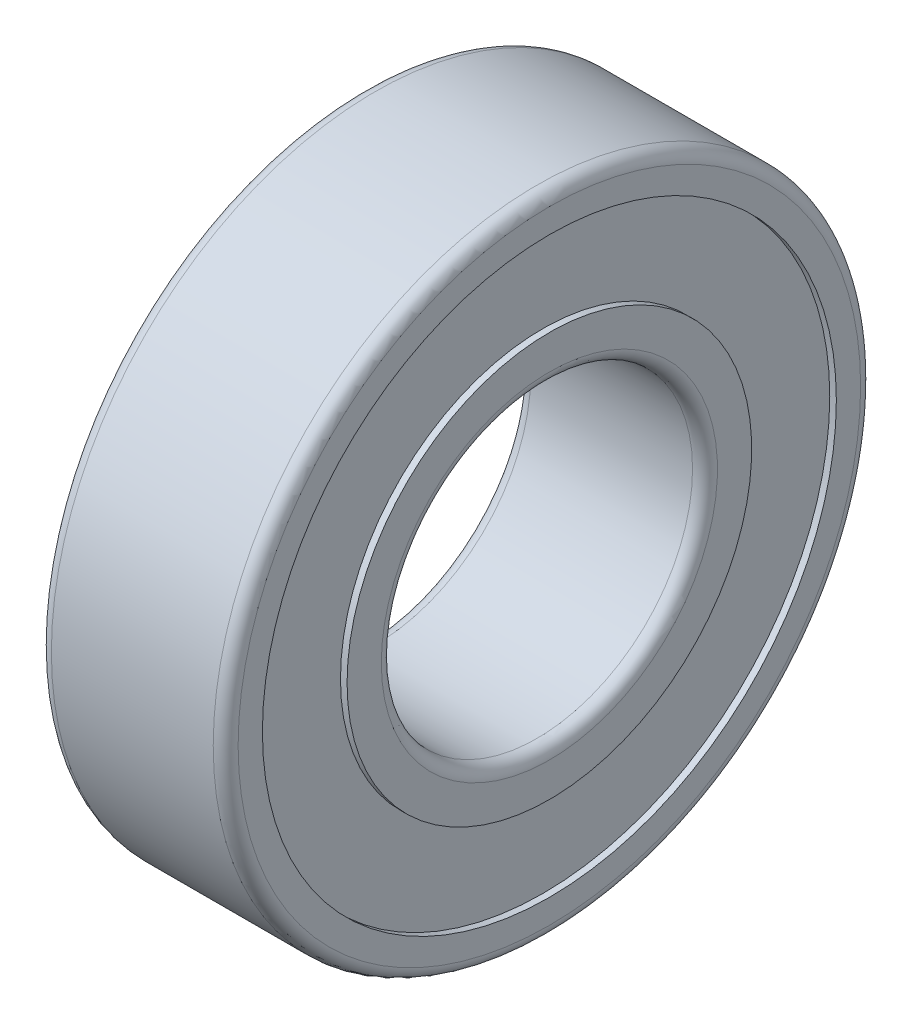
SolidWorks part; units mm, degrees
ref_plane "Plano frontal" through (0, 0, 0) normal (0, 0, 1) x (1, 0, 0)
ref_plane "Plano superior" through (0, 0, 0) normal (0, 1, 0) x (1, 0, 0)
ref_plane "Plano direito" through (0, 0, 0) normal (1, 0, 0) x (0, 0, -1)
ref_plane "Plane1" through (0, 0, 0) normal (0, 0, 1) x (1, 0, 0)
sketch "Sketch1" plane through (0, 0, 0) normal (0, 0, 1) x (1, 0, 0)
  line L0 (0, 25) -> (0, 23.05)
  line L1 (0, 23.05) -> (0.53, 23.05)
  line L2 (0.53, 23.05) -> (0.53, 16.25)
  line L3 (0.53, 16.25) -> (0, 16.25)
  line L4 (0, 16.25) -> (0, 13.5)
  line L5 (1, 12.5) -> (14, 12.5)
  line L6 (15, 13.5) -> (15, 16.25)
  line L7 (15, 16.25) -> (14.47, 16.25)
  line L8 (14.47, 16.25) -> (14.47, 23.05)
  line L9 (14.47, 23.05) -> (15, 23.05)
  line L10 (15, 23.05) -> (15, 25)
  line L11 (14, 26) -> (1, 26)
  line L12 (15, 0) -> (0, 0) construction
  arc A0 (0, 13.5) -> (1, 12.5) centre (1, 13.5) ccw
  arc A1 (14, 12.5) -> (15, 13.5) centre (14, 13.5) ccw
  arc A2 (15, 25) -> (14, 26) centre (14, 25) ccw
  arc A3 (1, 26) -> (0, 25) centre (1, 25) ccw
revolve "Revolve1" add sketch "Sketch1" angle 360 about L12
